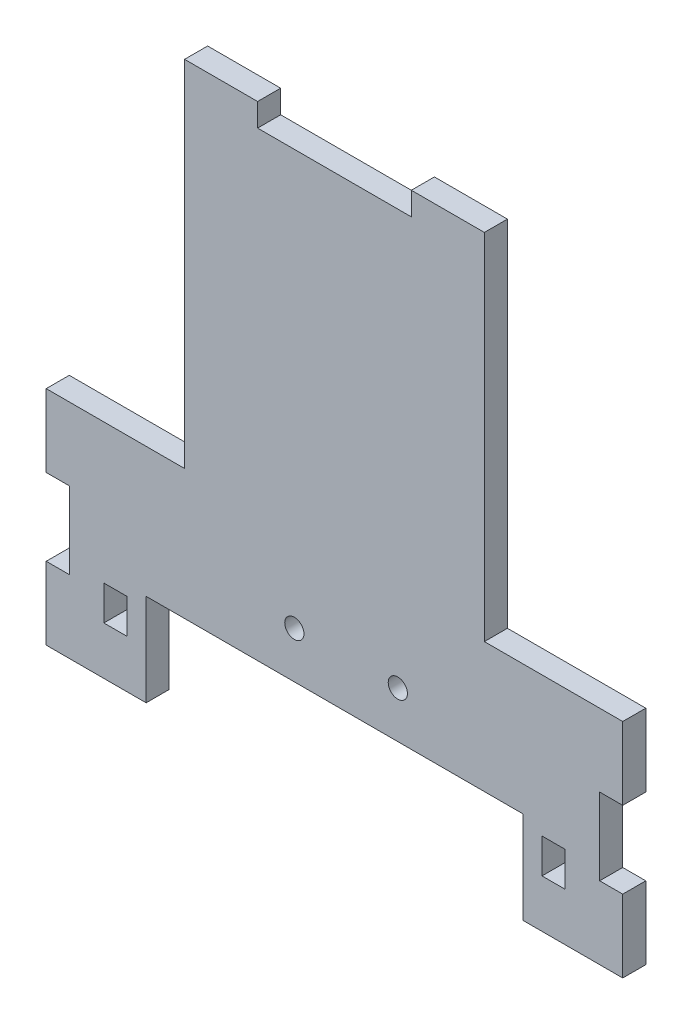
SolidWorks part; units mm, degrees
ref_plane "Alzado" through (0, 0, 0) normal (0, 0, 1) x (1, 0, 0)
ref_plane "Planta" through (0, 0, 0) normal (0, 1, 0) x (1, 0, 0)
ref_plane "Vista lateral" through (0, 0, 0) normal (1, 0, 0) x (0, 0, -1)
sketch "Croquis1" plane through (0, 0, 0) normal (0, 0, 1) x (1, 0, 0)
  line L1 (0, 28.9) -> (18, 28.9)
  line L2 (18, 28.9) -> (18, 75)
  line L4 (57, 75) -> (57, 28.9)
  line L5 (57, 28.9) -> (75, 28.9)
  line L7 (75, 0) -> (0, 0)
  line L8 (18, 75) -> (27.5, 75)
  line L9 (27.5, 75) -> (27.5, 72)
  line L10 (27.5, 72) -> (47.5, 72)
  line L11 (47.5, 72) -> (47.5, 75)
  line L12 (47.5, 75) -> (57, 75)
  line L21 (75, 28.9) -> (75, 19.45)
  line L25 (75, 9.45) -> (75, 0)
  line L26 (0, 28.9) -> (0, 19.45)
  line L30 (0, 9.45) -> (0, 0)
  line L31 (75, 19.45) -> (72, 19.45)
  line L32 (72, 19.45) -> (72, 9.45)
  line L33 (72, 9.45) -> (75, 9.45)
  line L35 (0, 19.45) -> (3, 19.45)
  line L36 (3, 19.45) -> (3, 9.45)
  line L37 (3, 9.45) -> (0, 9.45)
  dimension "D1" = 75
  dimension "D2" = 3
  dimension "D3" = 18
  dimension "D4" = 18
  dimension "D5" = 46.1
  dimension "D6" = 46.1
  dimension "D7" = 3
  dimension "D8" = 3
extrude "Saliente-Extruir1" add sketch "Croquis1" along normal blind 3
sketch "Croquis4" plane through (0, 0, 3) normal (0, 0, 1) x (1, 0, 0)
  line L0 (0, 0) -> (75, 0) construction
  line L1 (13, 0) -> (62, 0)
  line L2 (13, 0) -> (13, 12)
  line L3 (13, 12) -> (62, 12)
  line L4 (62, 0) -> (62, 12)
  line L7 (75, 0) -> (75, 9.45) construction
  line L8 (0, 9.45) -> (0, 0) construction
  dimension "D1" = 13
  dimension "D2" = 13
  dimension "D3" = 12
extrude "Cortar-Extruir2" cut sketch "Croquis4" against normal blind 10
sketch "Croquis5" plane through (0, 0, 0) normal (0, 0, -1) x (-1, 0, 0)
  circle A0 centre (-32.2797, 18.0333) radius 1.25
  circle A1 centre (-45.7417, 18.0333) radius 1.25
  dimension "D1" = 2.5
  dimension "D2" = 2.5
extrude "Cortar-Extruir3" cut sketch "Croquis5" against normal blind 10
sketch "Croquis6" plane through (0, 0, 0) normal (0, 0, -1) x (-1, 0, 0)
  line L1 (-7.5, 6.25) -> (-10.5, 6.25)
  line L2 (-7.5, 6.25) -> (-7.5, 10.75)
  line L3 (-7.5, 10.75) -> (-10.5, 10.75)
  line L4 (-10.5, 6.25) -> (-10.5, 10.75)
  line L5 (-64.5, 6.25) -> (-67.5, 6.25)
  line L6 (-64.5, 6.25) -> (-64.5, 10.75)
  line L7 (-64.5, 10.75) -> (-67.5, 10.75)
  line L8 (-67.5, 6.25) -> (-67.5, 10.75)
extrude "Cortar-Extruir4" cut sketch "Croquis6" against normal blind 10
